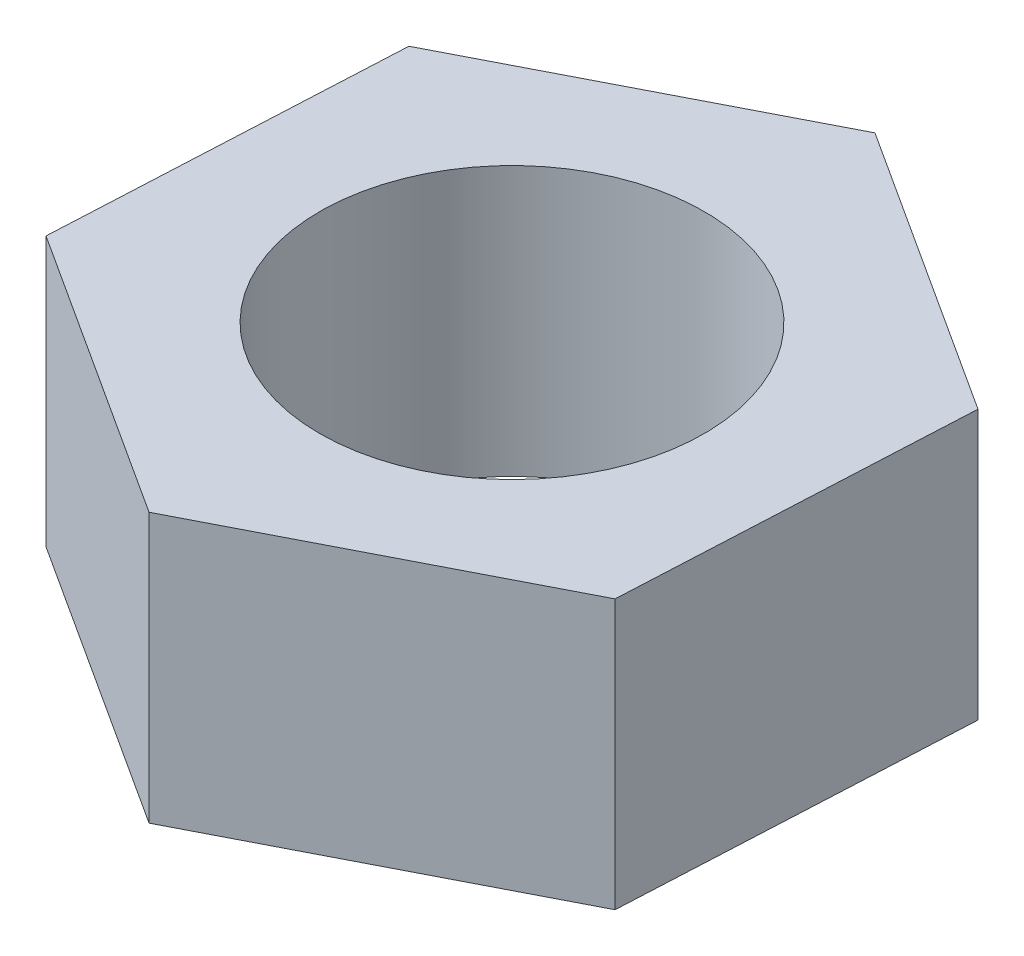
SolidWorks part; units mm, degrees
ref_plane "Спереди" through (0, 0, 0) normal (0, 0, 1) x (1, 0, 0)
ref_plane "Сверху" through (0, 0, 0) normal (0, 1, 0) x (1, 0, 0)
ref_plane "Справа" through (0, 0, 0) normal (1, 0, 0) x (0, 0, -1)
sketch "Эскиз1" plane through (0, 0, 0) normal (0, 1, 0) x (1, 0, 0)
  line L1 (3.7805, -2.4408) -> (4.0041, 2.0536)
  line L2 (4.0041, 2.0536) -> (0.2236, 4.4944)
  line L3 (0.2236, 4.4944) -> (-3.7805, 2.4408)
  line L4 (-3.7805, 2.4408) -> (-4.0041, -2.0536)
  line L5 (-4.0041, -2.0536) -> (-0.2236, -4.4944)
  line L6 (-0.2236, -4.4944) -> (3.7805, -2.4408)
  circle A0 centre (0, 0) radius 4.5 construction
  circle A1 centre (0, 0) radius 3.8971 construction
  dimension "D1" = 9
extrude "Вытянуть1" add sketch "Эскиз1" along normal blind 3.5
sketch "Эскиз2" plane through (0, 3.5, 0) normal (0, 1, 0) x (1, 0, 0)
  circle A0 centre (0, 0) radius 2.5
  dimension "D1" = 5
extrude "Вытянуть2" cut sketch "Эскиз2" against normal blind 3.5
